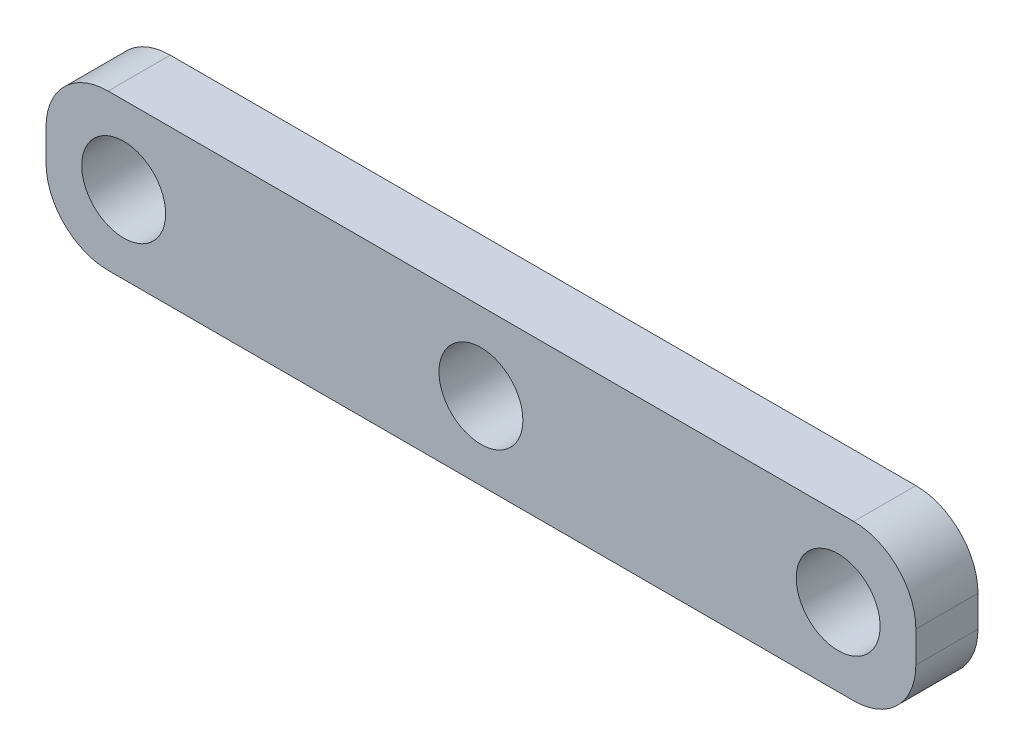
SolidWorks part; units mm, degrees
material "Thornel Mat VMA"
ref_plane "前视基准面" through (0, 0, 0) normal (0, 0, 1) x (1, 0, 0)
ref_plane "上视基准面" through (0, 0, 0) normal (0, 1, 0) x (1, 0, 0)
ref_plane "右视基准面" through (0, 0, 0) normal (1, 0, 0) x (0, 0, -1)
sketch "草图1" plane through (0, 0, 0) normal (0, 0, 1) x (1, 0, 0)
  line L0 (0, 2.5) -> (0, -2.5) construction
  line L1 (-14, -2.5) -> (14, -2.5)
  line L2 (-14, -2.5) -> (-14, 2.5)
  line L3 (-14, 2.5) -> (14, 2.5)
  line L4 (14, -2.5) -> (14, 2.5)
  line L5 (-14, -2.5) -> (14, 2.5) construction
  line L6 (-14, 2.5) -> (14, -2.5) construction
  circle A0 centre (-11.5, 0) radius 1.35
  circle A1 centre (11.5, 0) radius 1.35
  circle A2 centre (0, 0) radius 1.35
  point P0 (0, 0)
  dimension "D3" = 2.5
  dimension "D4" = 2.7
  dimension "D1" = 28
  dimension "D2" = 5
extrude "凸台-拉伸1" add sketch "草图1" along normal blind 2
fillet "圆角1" radius 2 4 edges at (14, -2.5, 1) (-14, -2.5, 1) (-14, 2.5, 1) (14, 2.5, 1)
